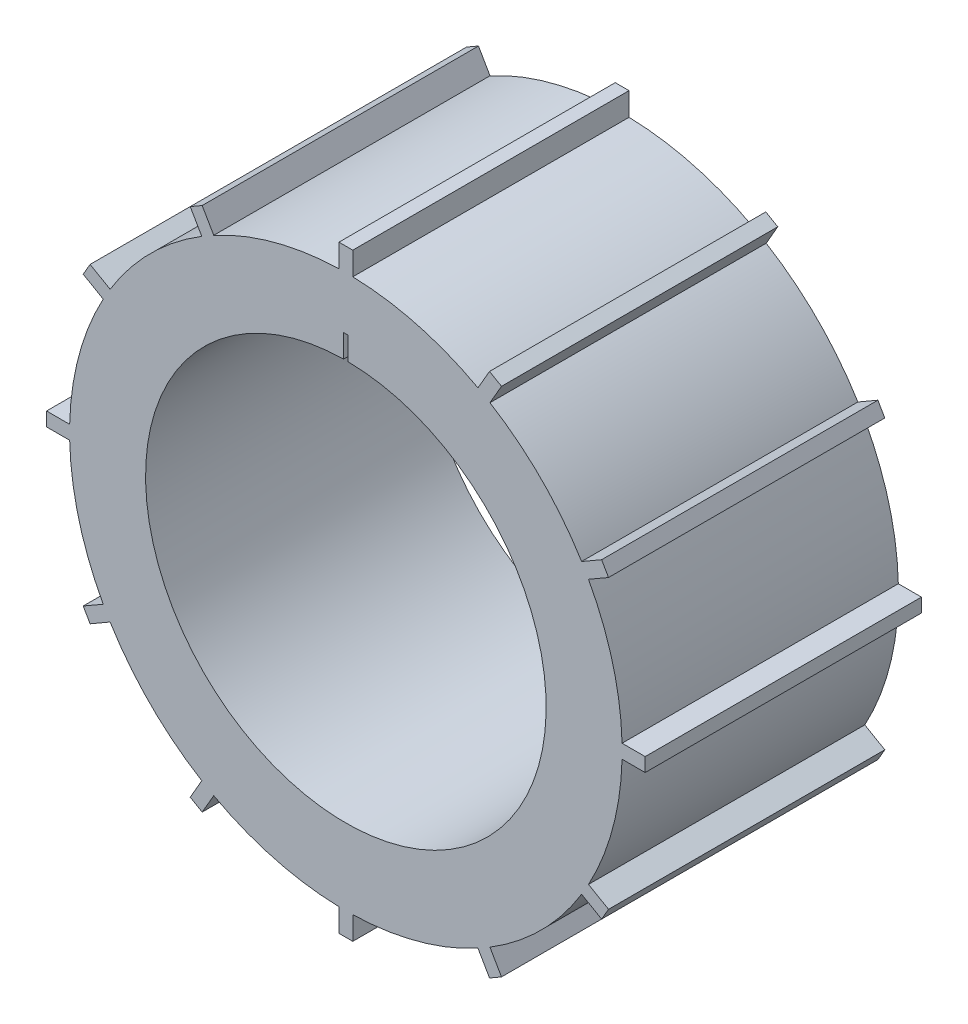
SolidWorks part; units mm, degrees
ref_plane "Front Plane" through (0, 0, 0) normal (0, 0, 1) x (1, 0, 0)
ref_plane "Top Plane" through (0, 0, 0) normal (0, 1, 0) x (1, 0, 0)
ref_plane "Right Plane" through (0, 0, 0) normal (1, 0, 0) x (0, 0, -1)
ref_plane "Plane1"
sketch "Sketch1" plane through (0, 0, 0) normal (0, 0, 1) x (1, 0, 0)
  circle A0 centre (0, 0) radius 60
  circle A1 centre (0, 0) radius 43.5
  dimension "D1" = 87
  dimension "D2" = 120
extrude "Extrusion1" add sketch "Sketch1" along normal blind 60 contours A0 A1
ref_plane "Plane2"
ref_plane "Plane3"
sketch "Sketch3" plane through (0, 0, 60) normal (0, 0, 1) x (1, 0, 0)
  line L0 (-0.5, 48.5) -> (-0.5, 43.4971)
  line L1 (0.5, 43.4971) -> (0.5, 48.5)
  line L2 (0.5, 48.5) -> (-0.5, 48.5)
  arc A0 (0.5, 43.4971) -> (-0.5, 43.4971) centre (0, 0) ccw
extrude "Extrusion3" cut sketch "Sketch3" against normal blind 60
sketch "Sketch4" plane through (0, 0, 60) normal (0, 0, 1) x (1, 0, 0)
  line L0 (31.2897, 51.1953) -> (31.299, 51.2115)
  line L1 (31.299, 51.2115) -> (33.799, 55.5417)
  line L2 (1.5, 59.9812) -> (1.5, 60)
  line L3 (1.5, 60) -> (1.5, 65)
  line L4 (-1.5, 59.9812) -> (-1.5, 60)
  line L5 (-1.5, 60) -> (-1.5, 65)
  line L6 (-1.5, 65) -> (1.5, 65)
  line L7 (28.6916, 52.6953) -> (28.701, 52.7115)
  line L8 (28.701, 52.7115) -> (31.201, 57.0417)
  line L9 (31.201, 57.0417) -> (33.799, 55.5417)
  line L10 (52.6953, 28.6916) -> (52.7115, 28.701)
  line L11 (52.7115, 28.701) -> (57.0417, 31.201)
  line L12 (51.1953, 31.2897) -> (51.2115, 31.299)
  line L13 (51.2115, 31.299) -> (55.5417, 33.799)
  line L14 (55.5417, 33.799) -> (57.0417, 31.201)
  line L15 (59.9812, -1.5) -> (60, -1.5)
  line L16 (60, -1.5) -> (65, -1.5)
  line L17 (59.9812, 1.5) -> (60, 1.5)
  line L18 (60, 1.5) -> (65, 1.5)
  line L19 (65, 1.5) -> (65, -1.5)
  line L20 (51.1953, -31.2897) -> (51.2115, -31.299)
  line L21 (51.2115, -31.299) -> (55.5417, -33.799)
  line L22 (52.6953, -28.6916) -> (52.7115, -28.701)
  line L23 (52.7115, -28.701) -> (57.0417, -31.201)
  line L24 (57.0417, -31.201) -> (55.5417, -33.799)
  line L25 (28.6916, -52.6953) -> (28.701, -52.7115)
  line L26 (28.701, -52.7115) -> (31.201, -57.0417)
  line L27 (31.2897, -51.1953) -> (31.299, -51.2115)
  line L28 (31.299, -51.2115) -> (33.799, -55.5417)
  line L29 (33.799, -55.5417) -> (31.201, -57.0417)
  line L30 (-1.5, -59.9812) -> (-1.5, -60)
  line L31 (-1.5, -60) -> (-1.5, -65)
  line L32 (1.5, -59.9812) -> (1.5, -60)
  line L33 (1.5, -60) -> (1.5, -65)
  line L34 (1.5, -65) -> (-1.5, -65)
  line L35 (-31.2897, -51.1953) -> (-31.299, -51.2115)
  line L36 (-31.299, -51.2115) -> (-33.799, -55.5417)
  line L37 (-28.6916, -52.6953) -> (-28.701, -52.7115)
  line L38 (-28.701, -52.7115) -> (-31.201, -57.0417)
  line L39 (-31.201, -57.0417) -> (-33.799, -55.5417)
  line L40 (-52.6953, -28.6916) -> (-52.7115, -28.701)
  line L41 (-52.7115, -28.701) -> (-57.0417, -31.201)
  line L42 (-51.1953, -31.2897) -> (-51.2115, -31.299)
  line L43 (-51.2115, -31.299) -> (-55.5417, -33.799)
  line L44 (-55.5417, -33.799) -> (-57.0417, -31.201)
  line L45 (-59.9812, 1.5) -> (-60, 1.5)
  line L46 (-60, 1.5) -> (-65, 1.5)
  line L47 (-59.9812, -1.5) -> (-60, -1.5)
  line L48 (-60, -1.5) -> (-65, -1.5)
  line L49 (-65, -1.5) -> (-65, 1.5)
  line L50 (-51.1953, 31.2897) -> (-51.2115, 31.299)
  line L51 (-51.2115, 31.299) -> (-55.5417, 33.799)
  line L52 (-52.6953, 28.6916) -> (-52.7115, 28.701)
  line L53 (-52.7115, 28.701) -> (-57.0417, 31.201)
  line L54 (-57.0417, 31.201) -> (-55.5417, 33.799)
  line L55 (-28.6916, 52.6953) -> (-28.701, 52.7115)
  line L56 (-28.701, 52.7115) -> (-31.201, 57.0417)
  line L57 (-31.2897, 51.1953) -> (-31.299, 51.2115)
  line L58 (-31.299, 51.2115) -> (-33.799, 55.5417)
  line L59 (-33.799, 55.5417) -> (-31.201, 57.0417)
  arc A0 (31.2897, 51.1953) -> (28.6916, 52.6953) centre (0, 0) ccw
  arc A1 (1.5, 59.9812) -> (-1.5, 59.9812) centre (0, 0) ccw
  arc A2 (52.6953, 28.6916) -> (51.1953, 31.2897) centre (0, 0) ccw
  arc A3 (59.9812, -1.5) -> (59.9812, 1.5) centre (0, 0) ccw
  arc A4 (51.1953, -31.2897) -> (52.6953, -28.6916) centre (0, 0) ccw
  arc A5 (28.6916, -52.6953) -> (31.2897, -51.1953) centre (0, 0) ccw
  arc A6 (-1.5, -59.9812) -> (1.5, -59.9812) centre (0, 0) ccw
  arc A7 (-31.2897, -51.1953) -> (-28.6916, -52.6953) centre (0, 0) ccw
  arc A8 (-52.6953, -28.6916) -> (-51.1953, -31.2897) centre (0, 0) ccw
  arc A9 (-59.9812, 1.5) -> (-59.9812, -1.5) centre (0, 0) ccw
  arc A10 (-51.1953, 31.2897) -> (-52.6953, 28.6916) centre (0, 0) ccw
  arc A11 (-28.6916, 52.6953) -> (-31.2897, 51.1953) centre (0, 0) ccw
  point P7 (1.5, 0)
  point P10 (-1.5, 0)
  point P79 (0, 0)
  dimension "D1" = 12
extrude "Boss-Extrude1" add sketch "Sketch4" against normal blind 60
